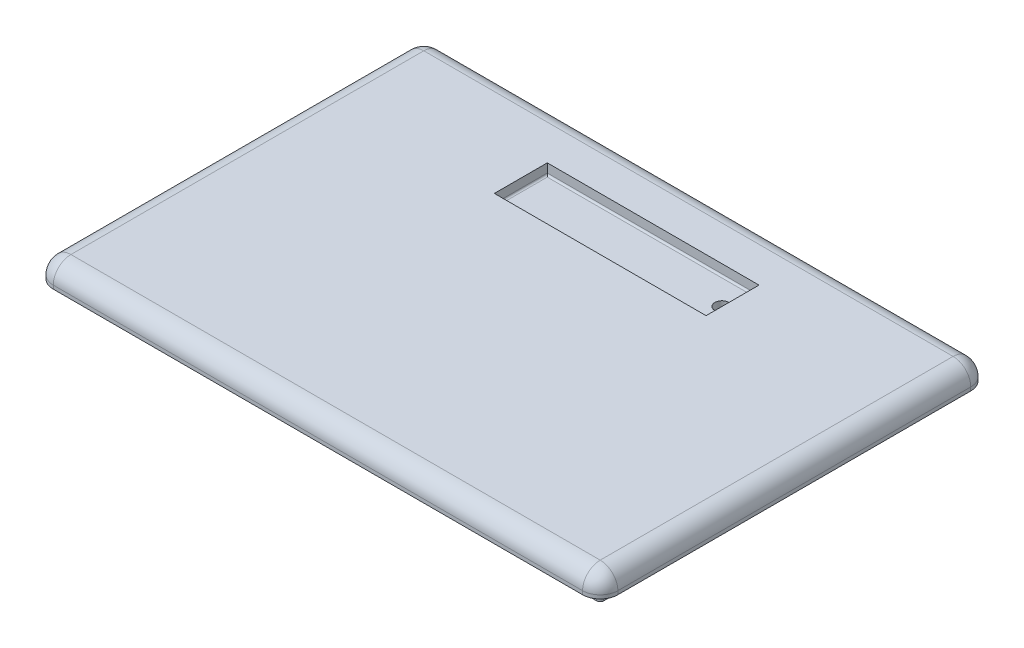
SolidWorks part; units mm, degrees
ref_plane "Front Plane" through (0, 0, 0) normal (0, 0, 1) x (1, 0, 0)
ref_plane "Top Plane" through (0, 0, 0) normal (0, 1, 0) x (1, 0, 0)
ref_plane "Right Plane" through (0, 0, 0) normal (1, 0, 0) x (0, 0, -1)
sketch "Sketch1" plane through (0, 0, 0) normal (0, 1, 0) x (1, 0, 0)
  line L1 (-80, 55) -> (80, 55)
  line L2 (-80, 55) -> (-80, -55)
  line L3 (-80, -55) -> (80, -55)
  line L4 (80, 55) -> (80, -55)
  line L5 (-80, 55) -> (80, -55) construction
  line L6 (-80, -55) -> (80, 55) construction
  point P0 (0, 0)
  dimension "D1" = 110
  dimension "D2" = 160
extrude "Boss-Extrude1" add sketch "Sketch1" along normal blind 6
fillet "Fillet1" radius 5 8 edges at (0, 6, 55) (-80, 6, 0) (0, 6, -55) (80, 6, 0) (-80, 3, 55) (80, 3, 55) (80, 3, -55) (-80, 3, -55)
sketch "Sketch2" plane through (0, 0, 0) normal (0, -1, 0) x (1, 0, 0)
  line L1 (-74.5, 49.5) -> (74.5, 49.5)
  line L2 (-74.5, 49.5) -> (-74.5, -49.5)
  line L3 (-74.5, -49.5) -> (74.5, -49.5)
  line L4 (74.5, 49.5) -> (74.5, -49.5)
  line L5 (-74.5, 49.5) -> (74.5, -49.5) construction
  line L6 (-74.5, -49.5) -> (74.5, 49.5) construction
  point P0 (0, 0)
  dimension "D1" = 99
  dimension "D2" = 149
extrude "Extrude-Thin1" add sketch "Sketch2" along normal blind 5 thin
fillet "Fillet2" radius 3 4 edges at (-71.5, 0, 0) (0, 0, 46.5) (71.5, 0, 0) (0, 0, -46.5)
fillet "Fillet3" radius 1 4 edges at (0, -5, -46.5) (71.5, -5, 0) (0, -5, 46.5) (-71.5, -5, 0)
sketch "Sketch3" plane through (-80, 0, 0) normal (-1, 0, 0) x (0, 0, 1)
  line L0 (-8, 0) -> (8, 0)
  line L1 (49.5, 0) -> (-49.5, 0) construction
  line L2 (-50, 0) -> (50, 0) construction
  line L4 (-5, 3) -> (5, 3)
  arc A1 (8, 0) -> (5, 3) centre (5, 0) ccw
  arc A2 (-8, 0) -> (-5, 3) centre (-5, 0) cw
  point P11 (0, 0)
  dimension "D2" = 3
  dimension "D1" = 3
  dimension "D3" = 16
  dimension "D4" = 10
revolve "Cut-Revolve1" cut sketch "Sketch3" angle 90 about L0
sketch "Sketch5" plane through (0, 6, 0) normal (0, 1, 0) x (1, 0, 0)
  line L0 (75, 50) -> (-75, 50) construction
  line L1 (-30, 40) -> (30, 40)
  line L2 (-30, 40) -> (-30, 25)
  line L3 (-30, 25) -> (30, 25)
  line L4 (30, 40) -> (30, 25)
  line L5 (-30, 40) -> (30, 25) construction
  line L6 (-30, 25) -> (30, 40) construction
  point P0 (0, 32.5)
  dimension "D1" = 60
  dimension "D2" = 15
  dimension "D3" = 10
extrude "Cut-Extrude1" cut sketch "Sketch5" against normal blind 3
fillet "Fillet4" radius 0.5 4 edges at (30, 3, -32.5) (0, 3, -25) (-30, 3, -32.5) (0, 3, -40)
sketch "Sketch6" plane through (0, 3, 0) normal (0, 1, 0) x (1, 0, 0)
  line L0 (30, 25) -> (30, 40) construction
  circle A0 centre (27, 32.5) radius 2
  point P4 (30, 32.5)
  dimension "D1" = 4
  dimension "D2" = 3
extrude "Cut-Extrude2" cut sketch "Sketch6" against normal blind 5
fillet "Fillet5" radius 1 4 edges at (74.5, -2.5, -49.5) (74.5, -2.5, 49.5) (-74.5, -2.5, 49.5) (-74.5, -2.5, -49.5)
